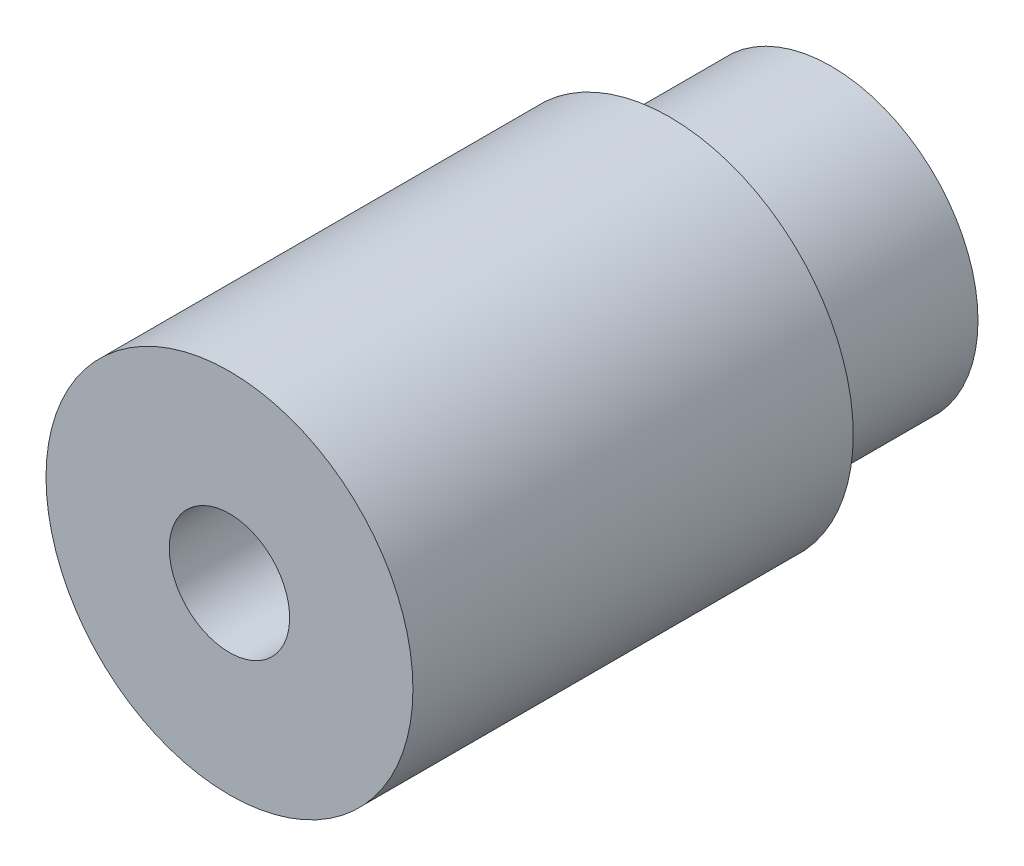
SolidWorks part; units mm, degrees
ref_plane "Front Plane" through (0, 0, 0) normal (0, 0, 1) x (1, 0, 0)
ref_plane "Top Plane" through (0, 0, 0) normal (0, 1, 0) x (1, 0, 0)
ref_plane "Right Plane" through (0, 0, 0) normal (1, 0, 0) x (0, 0, -1)
sketch "Sketch1" plane through (0, 0, 0) normal (0, 0, 1) x (1, 0, 0)
  circle A0 centre (25, -300) radius 12.5 construction
  circle A1 centre (25, -300) radius 12.5
extrude "Boss-Extrude1" add sketch "Sketch1" against normal blind 30
sketch "Sketch2" plane through (0, 0, -30) normal (0, 0, -1) x (-1, 0, 0)
  circle A0 centre (-25, -300) radius 10
  dimension "D1" = 20
extrude "Boss-Extrude2" add sketch "Sketch2" along normal blind 11
sketch "Sketch3" plane through (0, 0, -41) normal (0, 0, -1) x (-1, 0, 0)
  circle A0 centre (-25, -300) radius 4.1
extrude "Cut-Extrude1" cut sketch "Sketch3" against normal through all
cosmetic thread "Cosmetic Thread1" parameters "D2"=10
